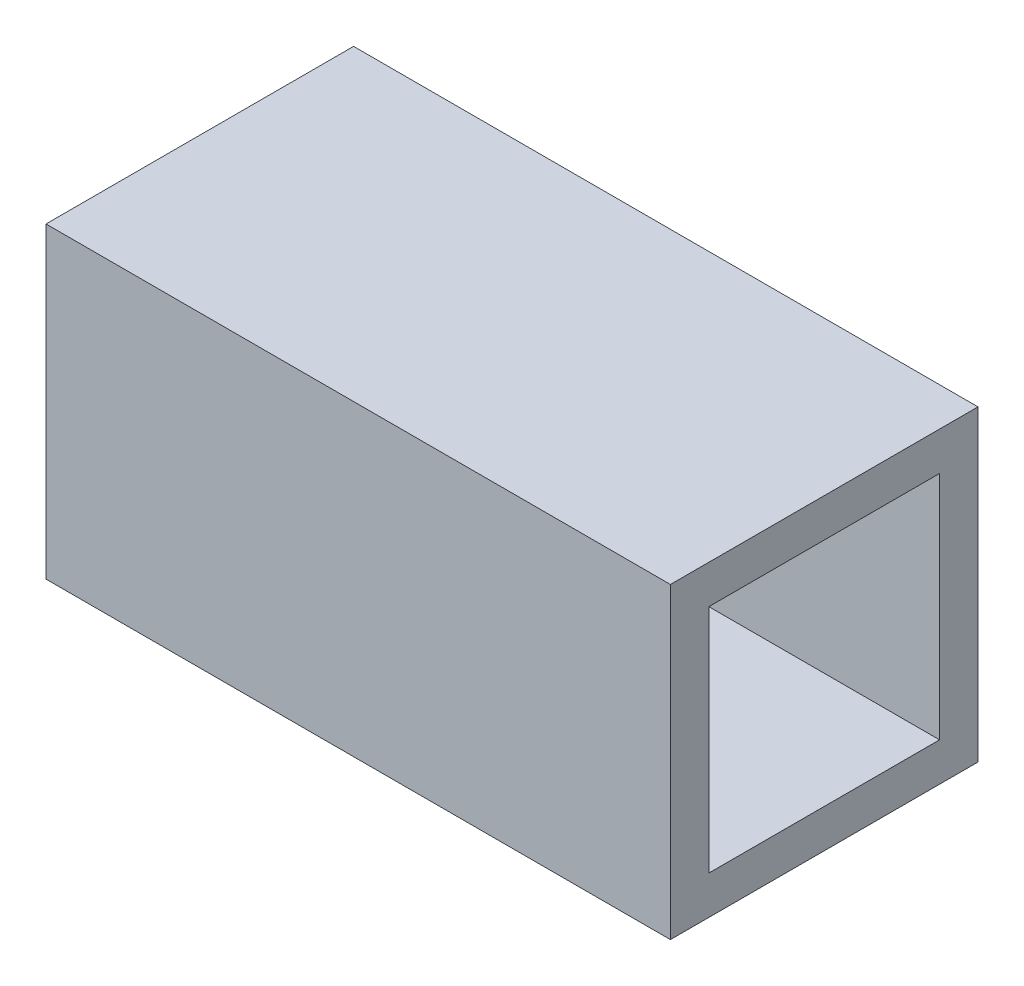
SolidWorks part; units mm, degrees
ref_plane "Front Plane" through (0, 0, 0) normal (0, 0, 1) x (1, 0, 0)
ref_plane "Top Plane" through (0, 0, 0) normal (0, 1, 0) x (1, 0, 0)
ref_plane "Right Plane" through (0, 0, 0) normal (1, 0, 0) x (0, 0, -1)
sketch "Sketch1" plane through (0, 0, 0) normal (0, 1, 0) x (1, 0, 0)
  line L1 (0, 0) -> (51.562, 0)
  line L2 (0, 0) -> (0, 25.4)
  line L3 (0, 25.4) -> (51.562, 25.4)
  line L4 (51.562, 0) -> (51.562, 25.4)
  dimension "D1" = 25.4
  dimension "D2" = 51.562
extrude "Boss-Extrude1" add sketch "Sketch1" along normal blind 25.4
sketch "Sketch2" plane through (51.562, 0, 0) normal (1, 0, 0) x (0, 0, -1)
  line L0 (25.4, 25.4) -> (25.4, 0) construction
  line L1 (3.175, 22.225) -> (22.225, 22.225)
  line L2 (3.175, 22.225) -> (3.175, 3.175)
  line L3 (3.175, 3.175) -> (22.225, 3.175)
  line L4 (22.225, 22.225) -> (22.225, 3.175)
  line L5 (0, 0) -> (25.4, 0) construction
  line L6 (0, 25.4) -> (0, 0) construction
  line L7 (0, 25.4) -> (25.4, 25.4) construction
  point P8 (0, 12.7)
  dimension "D1" = 3.175
  dimension "D2" = 3.175
  dimension "D3" = 3.175
  dimension "D4" = 3.175
extrude "Cut-Extrude1" cut sketch "Sketch2" against normal through all
sketch "Sketch3" plane through (0, 0, 0) normal (0, -1, 0) x (-1, 0, 0)
  line L0 (-51.562, 0) -> (-51.562, 25.4) construction
  circle A0 centre (-40.894, 14.2465) radius 3.175
  dimension "D1" = 6.35
  dimension "D2" = 10.668
